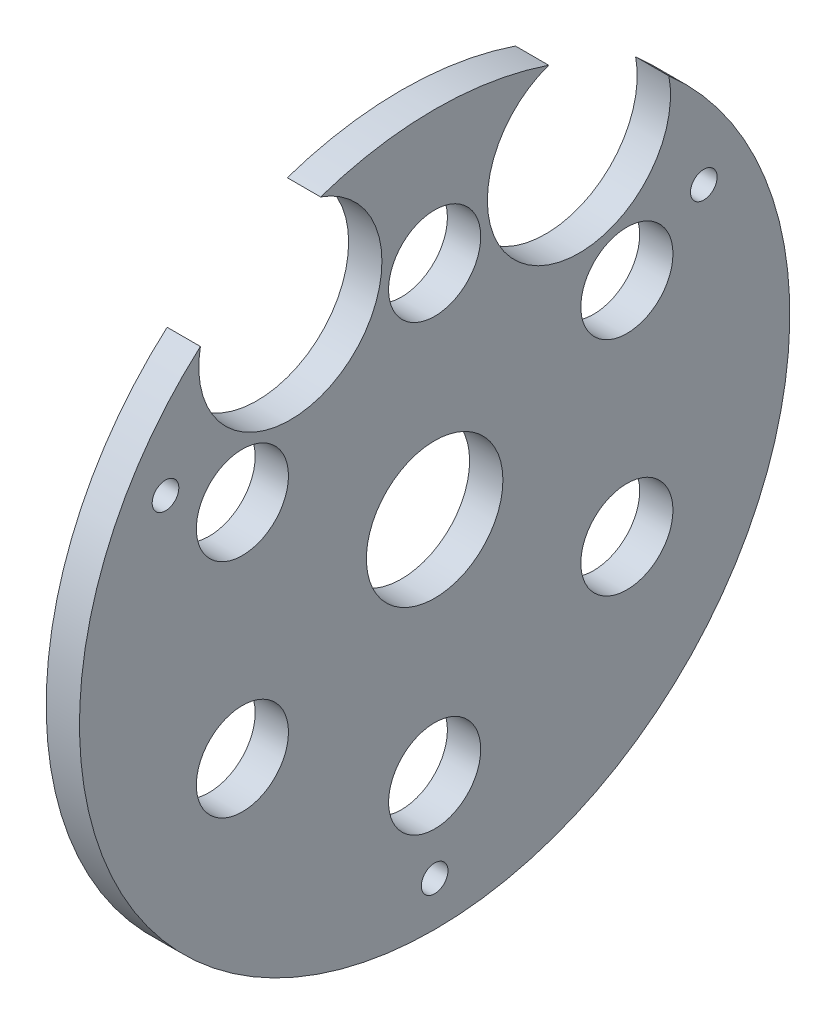
SolidWorks part; units mm, degrees
ref_plane "Front Plane" through (0, 0, 0) normal (0, 0, 1) x (1, 0, 0)
ref_plane "Top Plane" through (0, 0, 0) normal (0, 1, 0) x (1, 0, 0)
ref_plane "Right Plane" through (0, 0, 0) normal (1, 0, 0) x (0, 0, -1)
sketch "Axial blank profile" plane through (0, 0, 0) normal (0, 0, 1) x (1, 0, 0)
  line L0 (-60, 0) -> (30, 0) construction
  line L1 (-17, 0) -> (-14, 0)
  line L2 (-14, 0) -> (-14, 32)
  line L3 (-14, 32) -> (-17, 32)
  line L4 (-17, 32) -> (-17, 0)
revolve "Native revolved blank" add sketch "Axial blank profile" angle 360 about L0
sketch "Magnet-base locator bores sketch" plane through (0, 0, 0) normal (1, 0, 0) x (0, 0, -1)
  circle A0 centre (0, 0) radius 6.15
  circle A1 centre (0, 20) radius 4.15
  circle A2 centre (-17.3205, 10) radius 4.15
  circle A3 centre (-17.3205, -10) radius 4.15
  circle A4 centre (0, -20) radius 4.15
  circle A5 centre (17.3205, -10) radius 4.15
  circle A6 centre (17.3205, 10) radius 4.15
extrude "Magnet-base locator bores" cut sketch "Magnet-base locator bores sketch" along normal blind 3 from offset 17
sketch "Open fitting-route reliefs sketch" plane through (0, 0, 0) normal (1, 0, 0) x (0, 0, -1)
  circle A0 centre (-13, 22.5167) radius 8.25
  circle A1 centre (13, 22.5167) radius 8.25
extrude "Open fitting-route reliefs" cut sketch "Open fitting-route reliefs sketch" along normal blind 3 from offset 17
sketch "Three M2 locator clearance holes sketch" plane through (0, 0, 0) normal (1, 0, 0) x (0, 0, -1)
  circle A0 centre (-24.2487, 14) radius 1.2
  circle A1 centre (0, -28) radius 1.2
  circle A2 centre (24.2487, 14) radius 1.2
extrude "Three M2 locator clearance holes" cut sketch "Three M2 locator clearance holes sketch" along normal blind 3 from offset 17
